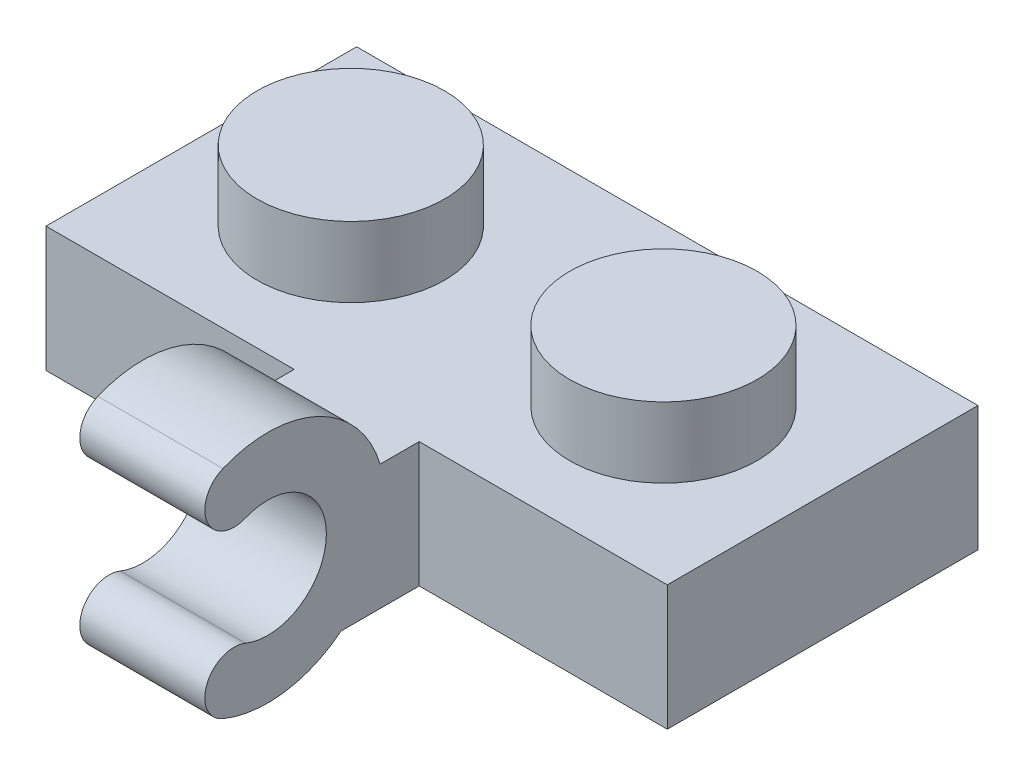
SolidWorks part; units mm, degrees
ref_plane "Front Plane" through (0, 0, 0) normal (0, 0, 1) x (1, 0, 0)
ref_plane "Top Plane" through (0, 0, 0) normal (0, 1, 0) x (1, 0, 0)
ref_plane "Right Plane" through (0, 0, 0) normal (1, 0, 0) x (0, 0, -1)
sketch "Sketch1" plane through (0, 0, 0) normal (0, 1, 0) x (1, 0, 0)
  line L1 (-7.95, -3.975) -> (7.95, -3.975)
  line L2 (-7.95, -3.975) -> (-7.95, 3.975)
  line L3 (-7.95, 3.975) -> (7.95, 3.975)
  line L4 (7.95, -3.975) -> (7.95, 3.975)
  line L5 (-7.95, -3.975) -> (7.95, 3.975) construction
  line L6 (-7.95, 3.975) -> (7.95, -3.975) construction
  point P0 (0, 0)
  dimension "D1" = 7.95
  dimension "D2" = 15.9
extrude "Boss-Extrude1" add sketch "Sketch1" along normal blind 3.2
shell "Shell1" thickness 1.2
sketch "Sketch3" plane through (0, 2, 0) normal (0, -1, 0) x (1, 0, 0)
  circle A0 centre (0, 0) radius 1.5
  circle A1 centre (0, 0) radius 0.5
  dimension "D1" = 3
  dimension "D2" = 1
extrude "Boss-Extrude3" add sketch "Sketch3" along normal up to surface (2 mm away) up to face at (0, 0, 0)
sketch "Sketch4" plane through (0, 3.2, 0) normal (0, 1, 0) x (1, 0, 0)
  line L2 (-7.95, -3.975) -> (7.95, -3.975) construction
  line L3 (-7.95, 3.975) -> (-7.95, -3.975) construction
  circle A1 centre (-4.05, -0.075) radius 2.4
  dimension "D1" = 3.9
  dimension "D3" = 4.8
  dimension "D2" = 3.9
extrude "Boss-Extrude4" add sketch "Sketch4" along normal blind 1.8
pattern_linear "LPattern1" count 2 spacing 8 along (1, 0, 0) of "Boss-Extrude4"
sketch "Sketch5" plane through (0, 0, 0) normal (1, 0, 0) x (0, 0, -1)
  line L0 (-3.975, 0) -> (-5.975, 0)
  line L1 (-3.975, 3.2) -> (-4.975, 3.2)
  line L2 (-7.8497, 2.3421) -> (-9.5143, -1.6766) construction
  line L3 (-7.8497, 2.3421) -> (-9.718, 6.8526) construction
  line L4 (-3.975, 3.2) -> (-3.975, 0)
  arc A0 (-8.9978, -0.4295) -> (-5.975, 0) centre (-7.8497, 2.3421) ccw
  arc A2 (-8.4237, 0.9563) -> (-8.4237, 3.7279) centre (-7.8497, 2.3421) ccw
  arc A3 (-8.9978, 5.1137) -> (-8.4237, 3.7279) centre (-8.7108, 4.4208) ccw
  arc A5 (-8.9978, -0.4295) -> (-8.4237, 0.9563) centre (-8.7108, 0.2634) cw
  arc A6 (-4.975, 3.2) -> (-8.9978, 5.1137) centre (-7.8497, 2.3421) ccw
  dimension "D3" = 3
  dimension "D4" = 6
  dimension "D1" = 1
  dimension "D2" = 2
  dimension "D5" = 135
extrude "Boss-Extrude5" add sketch "Sketch5" along normal mid plane 3.2
